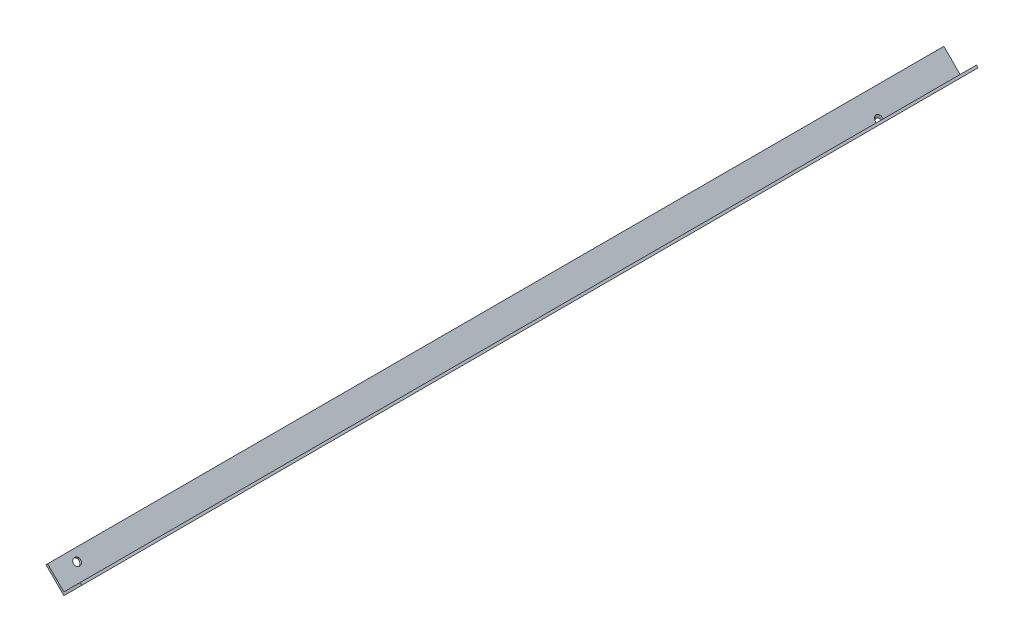
SolidWorks part; units mm, degrees
material "6061 Alloy"
ref_plane "Front Plane" through (0, 0, 0) normal (0, 0, 1) x (1, 0, 0)
ref_plane "Top Plane" through (0, 0, 0) normal (0, 1, 0) x (1, 0, 0)
ref_plane "Right Plane" through (0, 0, 0) normal (1, 0, 0) x (0, 0, -1)
sketch "Sketch1" plane through (0, 0, 0) normal (0, 0, 1) x (1, 0, 0)
  line L0 (0, 0) -> (-8.9803, 8.9803)
  line L1 (-8.9803, 8.9803) -> (-9.8783, 8.0822)
  line L2 (-9.8783, 8.0822) -> (0, -1.7961)
  line L3 (0, -1.7961) -> (9.8783, 8.0822)
  line L4 (9.8783, 8.0822) -> (8.9803, 8.9803)
  line L5 (8.9803, 8.9803) -> (0, 0)
  line L6 (-13.872, 0) -> (16.6117, 0) construction
  dimension "D1" = 1.27
  dimension "D2" = 12.7
extrude "Boss-Extrude1" add sketch "Sketch1" along normal blind 438.15 and the other way blind 57.15
sketch "Sketch2" plane through (0, 0, 0) normal (-0.7071, 0.7071, 0) x (0, 0, 1)
  line L0 (-57.15, 12.7) -> (438.15, 12.7) construction
  line L1 (438.15, 12.7) -> (438.15, 0) construction
  circle A0 centre (431.8, 7.62) radius 1.9844
  circle A1 centre (419.1, 7.62) radius 1.9844
  dimension "D2" = 3.9688
  dimension "D1" = 5.08
  dimension "D3" = 6.35
  dimension "D4" = 5.08
  dimension "D5" = 19.05
sketch "Sketch3" plane through (0, 0, 0) normal (0.7071, 0.7071, 0) x (0, 0, -1)
  line L0 (-438.15, 0) -> (-438.15, 12.7) construction
  line L1 (57.15, 12.7) -> (-438.15, 12.7) construction
  circle A0 centre (-425.45, 7.62) radius 1.9844
  dimension "D2" = 3.9688
  dimension "D1" = 12.7
  dimension "D3" = 5.08
extrude "Cut-Extrude1" cut sketch "Sketch2" against normal through all
extrude "Cut-Extrude2" cut sketch "Sketch3" against normal through all
sketch "Sketch4" plane through (0, 0, 0) normal (0, 1, 0) x (1, 0, 0)
  line L0 (0, -5.927) -> (0, 5.927) construction
  line L1 (-5.927, 0) -> (5.927, 0) construction
  circle A0 centre (0, 12.7) radius 1.9844
  dimension "D1" = 3.9688
  dimension "D2" = 12.7
extrude "Cut-Extrude3" cut sketch "Sketch4" against normal through all both and the other way through all
